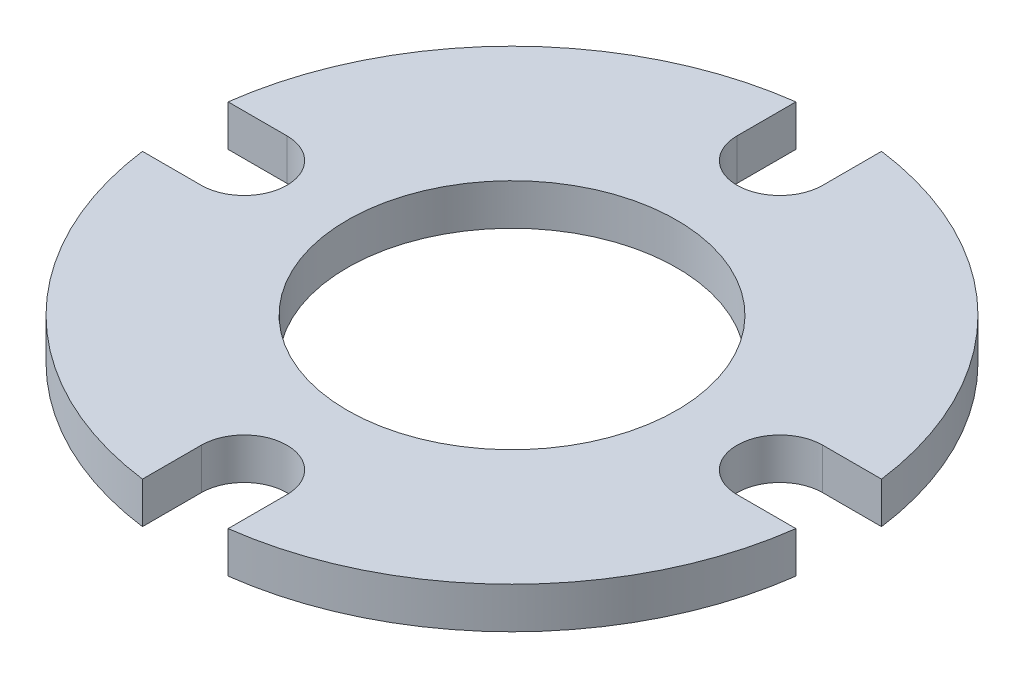
SolidWorks part; units mm, degrees
ref_plane "Front Plane" through (0, 0, 0) normal (0, 0, 1) x (1, 0, 0)
ref_plane "Top Plane" through (0, 0, 0) normal (0, 1, 0) x (1, 0, 0)
ref_plane "Right Plane" through (0, 0, 0) normal (1, 0, 0) x (0, 0, -1)
sketch "Sketch1" plane through (0, 0, 0) normal (0, 1, 0) x (1, 0, 0)
  line L0 (0, 1.2917) -> (0, -1.2917) construction
  line L1 (-1.5144, 0) -> (1.5144, 0) construction
  line L2 (0.813, 0.1616) -> (0.813, -0.1616) construction
  line L3 (0.813, 0.13) -> (0.9915, 0.13)
  line L4 (0.813, -0.13) -> (0.9915, -0.13)
  line L5 (0.13, -0.813) -> (0.13, -0.9915)
  line L6 (-0.13, -0.813) -> (-0.13, -0.9915)
  line L7 (-0.813, -0.13) -> (-0.9915, -0.13)
  line L8 (-0.813, 0.13) -> (-0.9915, 0.13)
  line L9 (-0.13, 0.813) -> (-0.13, 0.9915)
  line L10 (0.13, 0.813) -> (0.13, 0.9915)
  circle A0 centre (0, 0) radius 0.5
  arc A1 (0.9915, 0.13) -> (0.13, 0.9915) centre (0, 0) ccw
  arc A2 (0.813, 0.13) -> (0.813, -0.13) centre (0.813, 0) ccw
  arc A3 (0.13, -0.813) -> (-0.13, -0.813) centre (0, -0.813) ccw
  arc A4 (-0.813, -0.13) -> (-0.813, 0.13) centre (-0.813, 0) ccw
  arc A5 (-0.13, 0.813) -> (0.13, 0.813) centre (0, 0.813) ccw
  arc A6 (0.13, -0.9915) -> (0.9915, -0.13) centre (0, 0) ccw
  arc A7 (-0.9915, -0.13) -> (-0.13, -0.9915) centre (0, 0) ccw
  arc A8 (-0.13, 0.9915) -> (-0.9915, 0.13) centre (0, 0) ccw
  point P7 (0, 0)
  point P10 (0, 0)
  point P35 (0, 0)
  dimension "D1" = 2
  dimension "D2" = 1
  dimension "D4" = 0.26
  dimension "D3" = 0.813
  dimension "D5" = 4
extrude "Boss-Extrude1" add sketch "Sketch1" along normal mid plane 0.125
